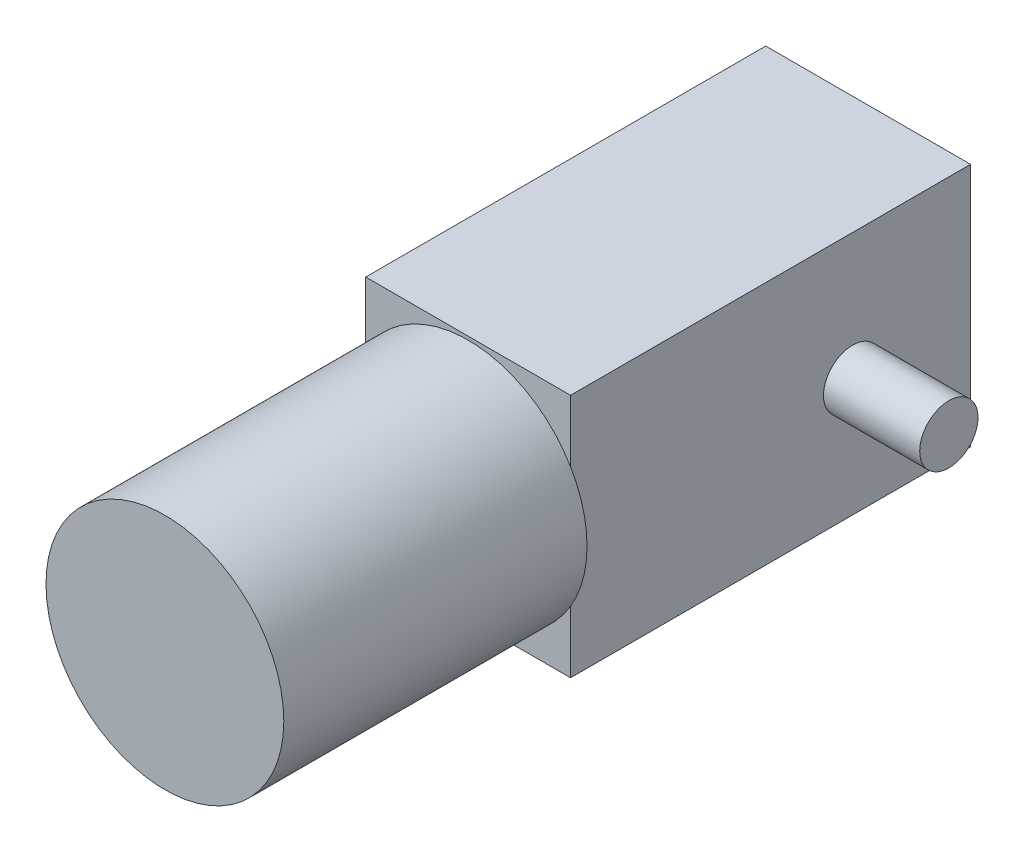
SolidWorks part; units mm, degrees
ref_plane "Front" through (0, 0, 0) normal (0, 0, 1) x (1, 0, 0)
ref_plane "Top" through (0, 0, 0) normal (0, 1, 0) x (1, 0, 0)
ref_plane "Right" through (0, 0, 0) normal (1, 0, 0) x (0, 0, -1)
sketch "Sketch1" plane through (0, 0, 0) normal (0, 0, 1) x (1, 0, 0)
  line L1 (0, 0) -> (18.923, 0)
  line L2 (0, 0) -> (0, 22.606)
  line L3 (0, 22.606) -> (18.923, 22.606)
  line L4 (18.923, 0) -> (18.923, 22.606)
  dimension "D1" = 22.606
  dimension "D2" = 18.923
extrude "Boss-Extrude1" add sketch "Sketch1" along normal blind 36.957
sketch "Sketch2" plane through (0, 0, 36.957) normal (0, 0, 1) x (1, 0, 0)
  line L0 (18.923, 22.606) -> (0, 22.606) construction
  line L1 (18.923, 0) -> (18.923, 22.606) construction
  circle A0 centre (9.4615, 11.303) radius 10.9855
  point P5 (9.4615, 22.606)
  point P8 (18.923, 11.303)
  dimension "D1" = 21.971
extrude "Boss-Extrude2" add sketch "Sketch2" along normal blind 28.0162 contours A0
sketch "Sketch3" plane through (0, 0, 0) normal (0, 0, -1) x (-1, 0, 0)
  line L0 (-18.923, 22.606) -> (0, 22.606) construction
  line L1 (-10.8585, 13.843) -> (-8.0645, 13.843)
  line L2 (-10.8585, 13.843) -> (-10.8585, 8.763)
  line L3 (-10.8585, 8.763) -> (-8.0645, 8.763)
  line L4 (-8.0645, 13.843) -> (-8.0645, 8.763)
  line L5 (0, 22.606) -> (0, 0) construction
  point P6 (-9.4615, 22.606)
  point P7 (-9.4615, 13.843)
  point P10 (0, 11.303)
  point P11 (-8.0645, 11.303)
  dimension "D1" = 2.794
  dimension "D2" = 5.08
extrude "Boss-Extrude3" add sketch "Sketch3" along normal blind 5.08
sketch "Sketch4" plane through (18.923, 0, 0) normal (1, 0, 0) x (0, 0, -1)
  line L0 (0, 0) -> (0, 22.606) construction
  line L1 (-36.957, 0) -> (0, 0) construction
  circle A0 centre (-10.8966, 10.8966) radius 2.6924
  dimension "D3" = 5.3848
  dimension "D1" = 10.8966
  dimension "D2" = 10.8966
extrude "Boss-Extrude4" add sketch "Sketch4" along normal blind 8.89
ref_plane "Plane1" through (9.4615, 0, 0) normal (1, 0, 0) x (0, 0, -1)
mirror "Mirror1" about plane through (9.4615, 0, 0) normal (1, 0, 0) of "Boss-Extrude4"
